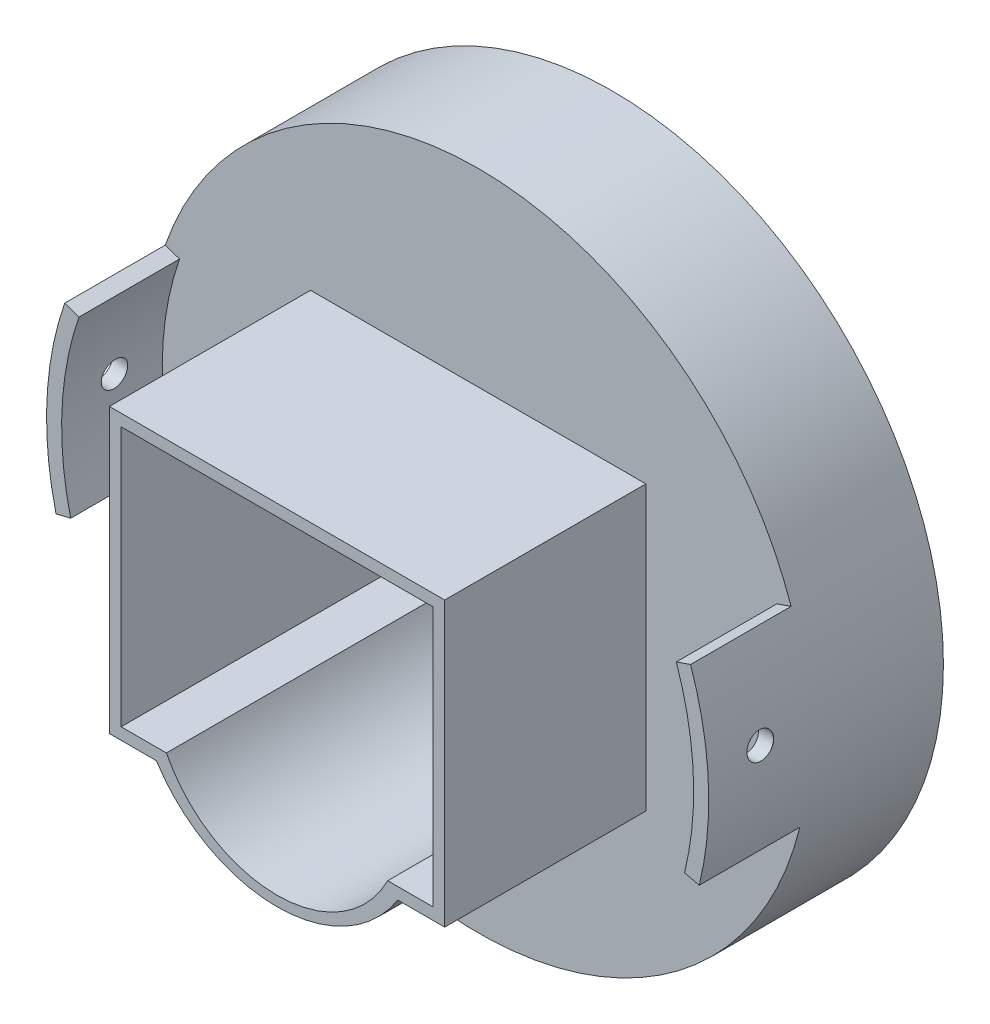
SolidWorks part; units mm, degrees
material "ABS"
ref_plane "Front Plane" through (0, 0, 0) normal (0, 0, 1) x (1, 0, 0)
ref_plane "Top Plane" through (0, 0, 0) normal (0, 1, 0) x (1, 0, 0)
ref_plane "Right Plane" through (0, 0, 0) normal (1, 0, 0) x (0, 0, -1)
sketch "Sketch1" plane through (0, 0, 0) normal (0, 0, 1) x (1, 0, 0)
  line L0 (16.764, -19.685) -> (23.622, -19.685)
  line L1 (-23.622, 19.685) -> (23.622, 19.685)
  line L2 (-23.622, 19.685) -> (-23.622, -19.685)
  line L3 (-23.622, -19.685) -> (-16.764, -19.685)
  line L4 (23.622, 19.685) -> (23.622, -19.685)
  line L5 (-23.622, 19.685) -> (23.622, -19.685) construction
  line L6 (-23.622, -19.685) -> (23.622, 19.685) construction
  circle A0 centre (0, 0) radius 50.165
  arc A1 (-16.764, -19.685) -> (16.764, -19.685) centre (0, -11.1845) ccw
  point P10 (0, 0)
  dimension "D1" = 100.33
  dimension "D5" = 18.796
  dimension "D2" = 47.244
  dimension "D3" = 39.37
  dimension "D4" = 6.858
extrude "Boss-Extrude1" add sketch "Sketch1" along normal blind 20.32
sketch "Sketch4" plane through (0, 0, 0) normal (0, 0, -1) x (-1, 0, 0)
  line L1 (-16.764, -19.685) -> (-23.622, -19.685)
  line L2 (-16.764, -19.685) -> (-16.764, 19.685)
  line L3 (-16.764, 19.685) -> (-23.622, 19.685)
  line L4 (-23.622, -19.685) -> (-23.622, 19.685)
  line L5 (16.764, -19.685) -> (23.622, -19.685)
  line L6 (16.764, -19.685) -> (16.764, 19.685)
  line L7 (16.764, 19.685) -> (23.622, 19.685)
  line L8 (23.622, -19.685) -> (23.622, 19.685)
extrude "Boss-Extrude3" add sketch "Sketch4" against normal blind 7.62
sketch "Sketch5" plane through (0, 0, 20.32) normal (0, 0, 1) x (1, 0, 0)
  line L0 (18.288, -21.463) -> (25.4, -21.463)
  line L1 (-25.4, -21.463) -> (-18.288, -21.463)
  line L2 (-25.4, -21.463) -> (-25.4, 21.463)
  line L3 (-25.4, 21.463) -> (25.4, 21.463)
  line L4 (25.4, -21.463) -> (25.4, 21.463)
  line L5 (-25.4, -21.463) -> (25.4, 21.463) construction
  line L6 (-25.4, 21.463) -> (25.4, -21.463) construction
  line L7 (-23.622, -19.685) -> (-16.764, -19.685)
  line L8 (-23.622, -19.685) -> (-23.622, 19.685)
  line L9 (-23.622, 19.685) -> (23.622, 19.685)
  line L10 (23.622, -19.685) -> (23.622, 19.685)
  line L11 (-23.622, -19.685) -> (23.622, 19.685) construction
  line L12 (-23.622, 19.685) -> (23.622, -19.685) construction
  line L14 (0, 0) -> (0, -31.496) construction
  line L15 (23.622, -19.685) -> (16.764, -19.685)
  arc A2 (-18.288, -21.463) -> (18.288, -21.463) centre (0, -9.812) ccw
  arc A4 (16.764, -19.685) -> (-16.764, -19.685) centre (0, -11.1845) cw
  point P0 (0, 0)
  point P6 (0, 0)
  dimension "D4" = 18.796
  dimension "D1" = 50.8
  dimension "D2" = 42.926
  dimension "D3" = 7.112
  dimension "D5" = 31.496
  dimension "D7" = 39.37
extrude "Boss-Extrude4" add sketch "Sketch5" along normal blind 30.48 contours L0 L4 L3 L2 L1
sketch "Sketch6" plane through (0, 0, 20.32) normal (0, 0, 1) x (1, 0, 0)
  line L0 (47.412, 16.3899) -> (45.2514, 15.6431)
  line L1 (48.7269, -11.9256) -> (46.5064, -11.3822)
  circle A0 centre (0, 0) radius 50.165 construction
  arc A1 (47.412, 16.3899) -> (48.7269, -11.9256) centre (0, 0) cw
  arc A2 (45.2514, 15.6431) -> (46.5064, -11.3822) centre (0, 0) cw
  dimension "D1" = 2.286
extrude "Boss-Extrude5" add sketch "Sketch6" along normal blind 15.24
hole_wizard "Ø4.0mm Dowel Hole1" positions "3DSketch3" profile "Sketch8" hole size "Ø4.0" standard "ANSI Metric"
sketch3d "3DSketch3"
  point P0 (50.0681, 3.116, 27.6474)
  point P3 (50.1007, 2.5394, 27.5641)
  point P4 (49.9606, 4.5243, 27.7306)
  point P5 (50.0681, 3.116, 27.6474)
sketch "Sketch8" plane through (50.0681, 3.116, 27.6474) normal (0, 0, 1) x (-0.0621, 0.9981, 0)
  line L0 (0, 0) -> (0, 5.0117)
  line L1 (0, 5.0117) -> (2, 3.81)
  line L2 (2, 3.81) -> (2, 0.021)
  line L3 (2, 0.021) -> (2.025, 0)
  line L5 (2.025, 0) -> (0, 0)
  line L6 (-2, 0.021) -> (-2.025, 0) construction
  line L10 (0, 5.0117) -> (-2, 3.81) construction
  line L11 (0, -6.35) -> (0, 107.95) construction
  dimension "Hole Dia." = 4
  dimension "Hole Depth" = 3.81
  dimension "Near C'Sink Dia." = 4.05
  dimension "Near C'Sink Angle" = 100
  dimension "Drill Angle" = 118
mirror "Mirror1" about plane through (0, 0, 0) normal (1, 0, 0) of "Ø4.0mm Dowel Hole1", "Boss-Extrude5"
